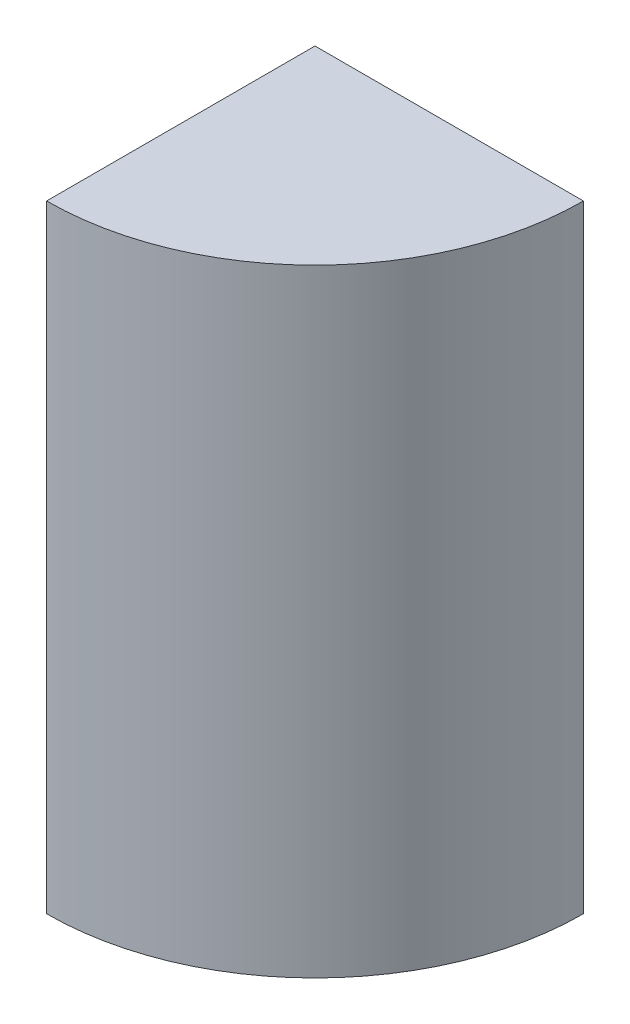
SolidWorks part; units mm, degrees
ref_plane "Front Plane" through (0, 0, 0) normal (0, 0, 1) x (1, 0, 0)
ref_plane "Top Plane" through (0, 0, 0) normal (0, 1, 0) x (1, 0, 0)
ref_plane "Right Plane" through (0, 0, 0) normal (1, 0, 0) x (0, 0, -1)
sketch "Sketch1" plane through (0, 0, 0) normal (0, 1, 0) x (1, 0, 0)
  line L0 (0, 0) -> (254, 0)
  line L1 (0, 0) -> (0, -254)
  arc A0 (254, 0) -> (0, -254) centre (0, 0) cw
extrude "Boss-Extrude1" add sketch "Sketch1" along normal blind 584.2 contours A0 L0 L1
